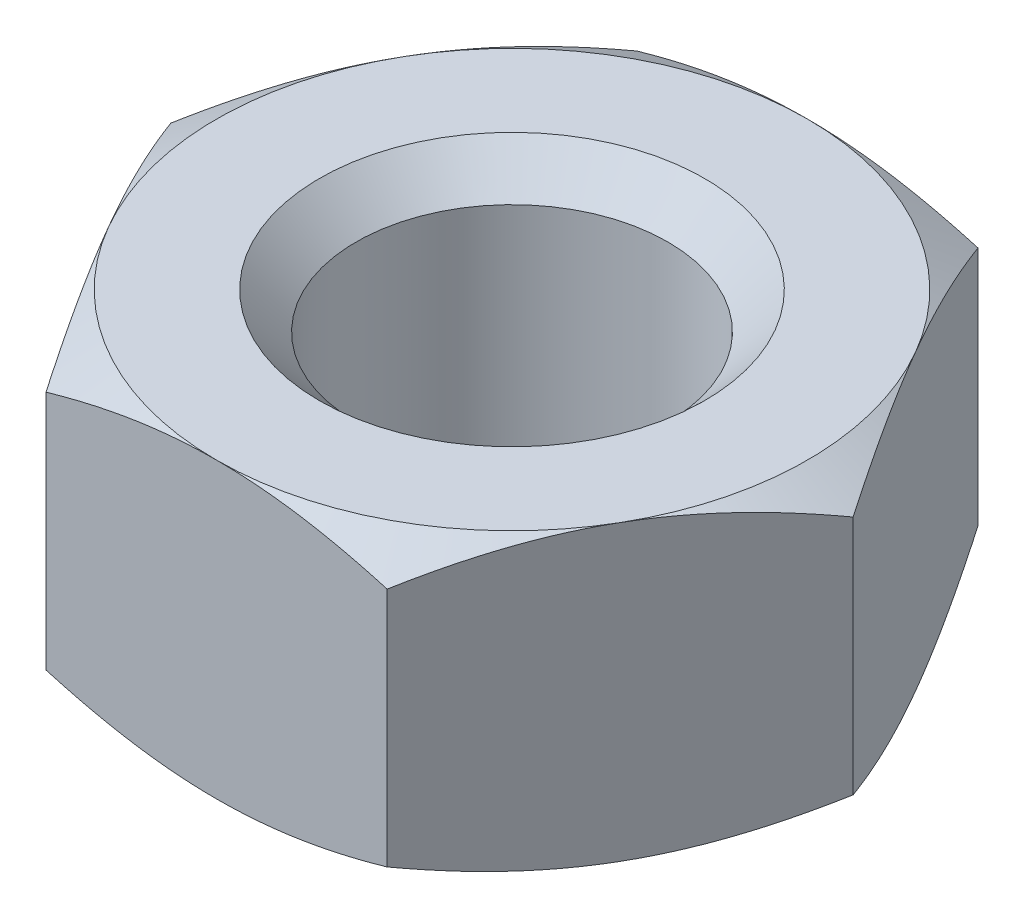
SolidWorks part; units mm, degrees
ref_plane "Front Plane" through (0, 0, 0) normal (0, 0, 1) x (1, 0, 0)
ref_plane "Top Plane" through (0, 0, 0) normal (0, 1, 0) x (1, 0, 0)
ref_plane "Right Plane" through (0, 0, 0) normal (1, 0, 0) x (0, 0, -1)
sketch "Эскиз1" plane through (0, 0, 0) normal (0, 1, 0) x (1, 0, 0)
  line L1 (9.3, 0) -> (4.65, 8.054)
  line L2 (4.65, 8.054) -> (-4.65, 8.054)
  line L3 (-4.65, 8.054) -> (-9.3, 0)
  line L4 (-9.3, 0) -> (-4.65, -8.054)
  line L5 (-4.65, -8.054) -> (4.65, -8.054)
  line L6 (4.65, -8.054) -> (9.3, 0)
  circle A0 centre (0, 0) radius 8.054 construction
  point P1 (0, 0)
  dimension "D1" = 18.6
extrude "Бобышка-Вытянуть1" add sketch "Эскиз1" along normal blind 8
sketch "Эскиз2" plane through (0, 8, 0) normal (0, 1, 0) x (1, 0, 0)
  line L0 (-4.65, 8.054) -> (-9.3, 0) construction
  circle A0 centre (0, 0) radius 8.054
extrude "Вырез-Вытянуть2" cut sketch "Эскиз2" against normal blind 8 draft 60 flip side to cut
sketch "Эскиз3" plane through (0, 0, 0) normal (0, -1, 0) x (1, 0, 0)
  line L0 (-9.3, 0) -> (-4.65, 8.054) construction
  circle A0 centre (0, 0) radius 8.054
extrude "Вырез-Вытянуть3" cut sketch "Эскиз3" against normal blind 8 draft 60 flip side to cut
sketch "Эскиз4" plane through (0, 0, 0) normal (0, -1, 0) x (1, 0, 0)
  circle A0 centre (0, 0) radius 4.25
  dimension "D1" = 8.5
extrude "Вырез-Вытянуть4" cut sketch "Эскиз4" against normal through all
chamfer "Фаска1" distance 1 angle 45 2 edges at (0, 8, -4.25) (0, 0, -4.25)
